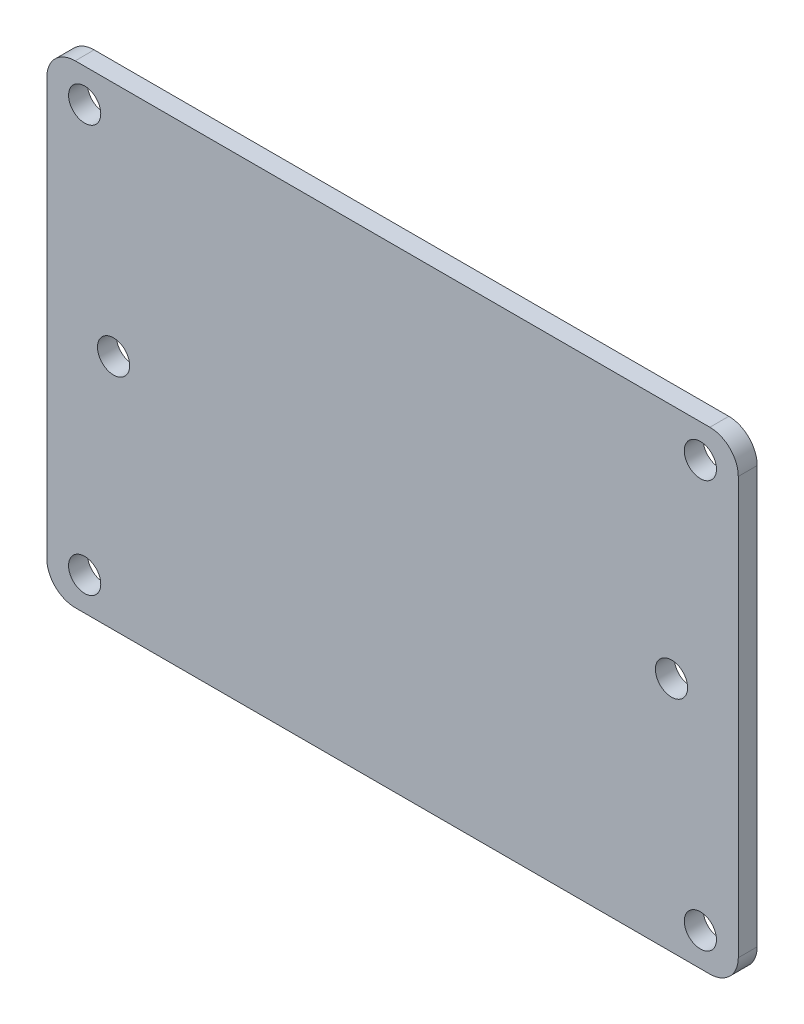
SolidWorks part; units mm, degrees
ref_plane "Front Plane" through (0, 0, 0) normal (0, 0, 1) x (1, 0, 0)
ref_plane "Top Plane" through (0, 0, 0) normal (0, 1, 0) x (1, 0, 0)
ref_plane "Right Plane" through (0, 0, 0) normal (1, 0, 0) x (0, 0, -1)
sketch "Sketch1" plane through (0, 0, 0) normal (0, 0, 1) x (1, 0, 0)
  line L0 (-32.5, 0) -> (0, 0) construction
  line L1 (-33.5, 25) -> (33.5, 25)
  line L2 (-36.5, 22) -> (-36.5, -22)
  line L3 (-33.5, -25) -> (33.5, -25)
  line L4 (36.5, 22) -> (36.5, -22)
  line L5 (-36.5, 25) -> (36.5, -25) construction
  line L6 (-36.5, -25) -> (36.5, 25) construction
  line L7 (-32.5, 0) -> (-32.5, -21.5) construction
  arc A3 (-33.5, 25) -> (-36.5, 22) centre (-33.5, 22) ccw
  arc A4 (-33.5, -25) -> (-36.5, -22) centre (-33.5, -22) cw
  arc A5 (36.5, -22) -> (33.5, -25) centre (33.5, -22) cw
  arc A6 (33.5, 25) -> (36.5, 22) centre (33.5, 22) cw
  circle A7 centre (-32.5, -21.5) radius 1.7
  point P0 (0, 0)
  dimension "D3" = 32.5
  dimension "D4" = 3.4
  dimension "D5" = 3
  dimension "D6" = 3
  dimension "D7" = 3
  dimension "D8" = 3
  dimension "D1" = 73
  dimension "D2" = 50
  dimension "D9" = 21.5
extrude "Boss-Extrude1" add sketch "Sketch1" along normal blind 2
sketch "Sketch3" plane through (0, 0, 0) normal (0, 0, 1) x (1, 0, 0)
  line L0 (0, 0) -> (32.5, 0) construction
  line L1 (32.5, 0) -> (32.5, -21.5) construction
  circle A1 centre (32.5, -21.5) radius 1.7
  dimension "D1" = 3.4
  dimension "D3" = 21.5
  dimension "D2" = 32.5
extrude "Cut-Extrude7" cut sketch "Sketch3" along normal up to next
sketch "Sketch4" plane through (0, 0, 2) normal (0, 0, 1) x (1, 0, 0)
  line L0 (0, 0) -> (-32.5, 0) construction
  line L1 (-32.5, 0) -> (-32.4978, 0.0203)
  line L2 (-32.5, 0) -> (-32.5, 21.5) construction
  circle A0 centre (-32.5, 21.5) radius 1.7
  dimension "D3" = 3.4
  dimension "D1" = 32.5
  dimension "D2" = 21.5
extrude "Cut-Extrude8" cut sketch "Sketch4" against normal through all contours A0
sketch "Sketch7" plane through (0, 0, 2) normal (0, 0, 1) x (1, 0, 0)
  line L0 (0, 0) -> (32.5, 0) construction
  line L1 (32.5, 0) -> (32.5, 21.5) construction
  circle A0 centre (32.5, 21.5) radius 1.7
  dimension "D3" = 3.4
  dimension "D1" = 32.5
  dimension "D2" = 21.5
extrude "Cut-Extrude9" cut sketch "Sketch7" against normal through all contours A0
sketch "Sketch8" plane through (0, 0, 0) normal (0, 0, -1) x (-1, 0, 0)
  circle A0 centre (-29.45, 0) radius 1.7
  circle A1 centre (29.45, 0) radius 1.7
  dimension "D1" = 3.4
  dimension "D2" = 3.4
  dimension "D3" = 58.9
extrude "Cut-Extrude10" cut sketch "Sketch8" against normal up to next
